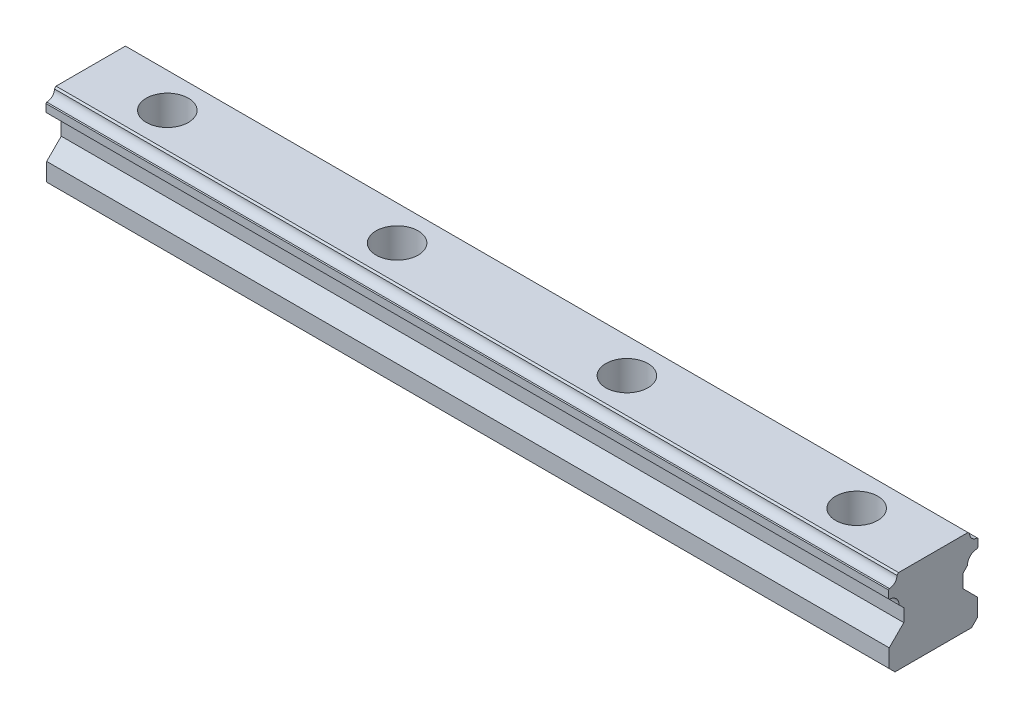
SolidWorks part; units mm, degrees
ref_plane "Front Plane" through (0, 0, 0) normal (0, 0, 1) x (1, 0, 0)
ref_plane "Top Plane" through (0, 0, 0) normal (0, 1, 0) x (1, 0, 0)
ref_plane "Right Plane" through (0, 0, 0) normal (1, 0, 0) x (0, 0, -1)
sketch "Sketch1" plane through (0, 0, 0) normal (1, 0, 0) x (0, 0, -1)
  line L0 (0, 0) -> (0, 22) construction
  line L1 (-10, 0) -> (10, 0)
  line L2 (10, 0) -> (11.5, 1.5)
  line L3 (11.5, 1.5) -> (11.5, 6.2)
  line L4 (11.5, 6.2) -> (7.7, 10)
  line L5 (7.7, 10) -> (7.7, 13.38)
  line L6 (7.7, 13.38) -> (8.93, 14.61)
  line L7 (11.46, 17.14) -> (8.93, 17.14) construction
  line L8 (11.46, 17.14) -> (11.68, 17.36)
  line L9 (11.68, 17.36) -> (11.68, 19.38)
  line L10 (11.68, 19.38) -> (11.47, 19.59)
  line L11 (8.93, 17.14) -> (8.93, 14.61) construction
  line L12 (9.48, 21.58) -> (9.06, 22)
  line L13 (9.06, 22) -> (-9.06, 22)
  line L14 (9.48, 21.58) -> (9.48, 19.59) construction
  line L15 (9.48, 19.59) -> (11.47, 19.59) construction
  line L16 (-9.48, 19.59) -> (-11.47, 19.59) construction
  line L17 (-9.48, 21.58) -> (-9.48, 19.59) construction
  line L18 (-8.93, 17.14) -> (-8.93, 14.61) construction
  line L19 (-11.46, 17.14) -> (-8.93, 17.14) construction
  line L20 (-9.48, 21.58) -> (-9.06, 22)
  line L21 (-11.68, 19.38) -> (-11.47, 19.59)
  line L22 (-11.68, 17.36) -> (-11.68, 19.38)
  line L23 (-11.46, 17.14) -> (-11.68, 17.36)
  line L24 (-7.7, 13.38) -> (-8.93, 14.61)
  line L25 (-7.7, 10) -> (-7.7, 13.38)
  line L26 (-11.5, 6.2) -> (-7.7, 10)
  line L27 (-11.5, 1.5) -> (-11.5, 6.2)
  line L28 (-10, 0) -> (-11.5, 1.5)
  arc A0 (9.48, 21.58) -> (11.47, 19.59) centre (11.47, 21.58) ccw
  arc A1 (11.46, 17.14) -> (8.93, 14.61) centre (11.46, 14.61) ccw
  arc A2 (-11.46, 17.14) -> (-8.93, 14.61) centre (-11.46, 14.61) cw
  arc A3 (-9.48, 21.58) -> (-11.47, 19.59) centre (-11.47, 21.58) cw
  dimension "D1" = 135
  dimension "D11" = 2.53
  dimension "D18" = 23
  dimension "D2" = 135
  dimension "D3" = 135
  dimension "D4" = 135
  dimension "D5" = 22
  dimension "D6" = 4.7
  dimension "D7" = 3.38
  dimension "D8" = 1.5
  dimension "D9" = 3.8
  dimension "D10" = 1.23
  dimension "D12" = 135
  dimension "D13" = 0.22
  dimension "D14" = 135
  dimension "D15" = 2.45
  dimension "D16" = 0.21
  dimension "D17" = 0.42
extrude "Boss-Extrude1" add sketch "Sketch1" along normal blind 220
ref_plane "Plane1" through (0, 0, 0) normal (0, 0, -1) x (-1, 0, 0)
hole_wizard "Bolt Hole" positions "3DSketch1" profile "Sketch2" counterbore size "M6" standard "ANSI Metric" end condition through all
sketch3d "3DSketch1"
  line L0 (0, 22, -9.06) -> (0, 22, 9.06) construction
  point P0 (20, 22, 0)
  dimension "D1" = 20
sketch "Sketch2" plane through (20, 22, 0) normal (1, 0, 0) x (0, 0, 1)
  line L0 (0, 0) -> (0, 22)
  line L1 (0, 22) -> (3.5, 22)
  line L3 (3.5, 22) -> (3.5, 9)
  line L4 (3.5, 9) -> (5.5, 9)
  line L5 (5.5, 9) -> (5.5, 0)
  line L7 (5.5, 0) -> (0, 0)
  line L11 (0, -6.35) -> (0, 107.95) construction
  dimension "Thru Hole Dia." = 7
  dimension "Thru Hole Depth" = 22
  dimension "C'Bore Dia." = 11
  dimension "C'Bore Depth" = 9
pattern_linear "Bolt Pattern" count 4 spacing 60 along (1, 0, 0) of "Bolt Hole"
